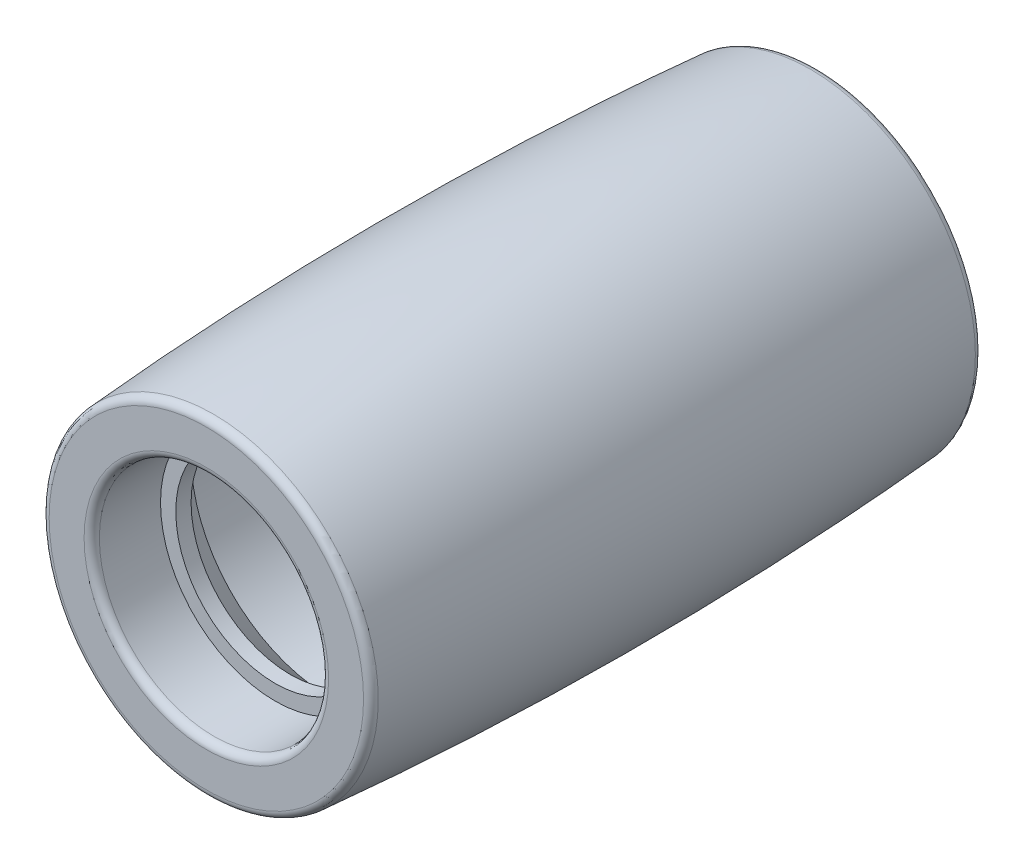
SolidWorks part; units mm, degrees
ref_plane "Ebene vorne" through (0, 0, 0) normal (0, 0, 1) x (1, 0, 0)
ref_plane "Ebene oben" through (0, 0, 0) normal (0, 1, 0) x (1, 0, 0)
ref_plane "Ebene rechts" through (0, 0, 0) normal (1, 0, 0) x (0, 0, -1)
sketch "Skizze1" plane through (0, 0, 0) normal (1, 0, 0) x (0, 0, -1)
  line L27 (0, 0) -> (99, 0) construction
  line L28 (89.5, 21.5) -> (89.5, 19.25) construction
  line L29 (81, 18.25) -> (83.1445, 19.25) construction
  line L30 (83.1445, 19.25) -> (89.5, 19.25) construction
  line L31 (42.3, 18.25) -> (81, 18.25) construction
  line L32 (42.3, 18.25) -> (42.3, 11) construction
  line L33 (42.3, 11) -> (39.3, 11) construction
  line L34 (39.3, 11) -> (39.3, 18.25) construction
  line L35 (20.5, 18.25) -> (39.3, 18.25) construction
  line L36 (20.5, 13) -> (27.7121, 20.2121) construction
  line L37 (18.5, 13) -> (20.5, 13) construction
  line L38 (18.5, 15) -> (18.5, 5) construction
  line L39 (18.5, 15) -> (9.5, 15) construction
  line L40 (9.5, 21.5) -> (9.5, 15) construction
  line L41 (0, 0) -> (99, 0) construction
  line L42 (89.5, 21.5) -> (89.5, 19.25)
  line L43 (81, 18.25) -> (83.1445, 19.25)
  line L44 (83.1445, 19.25) -> (89.5, 19.25)
  line L45 (42.3, 18.25) -> (81, 18.25)
  line L46 (42.3, 18.25) -> (42.3, 11)
  line L47 (42.3, 11) -> (39.3, 11)
  line L48 (39.3, 11) -> (39.3, 18.25)
  line L49 (25.75, 18.25) -> (39.3, 18.25)
  line L50 (20.5, 13) -> (25.75, 18.25)
  line L51 (18.5, 13) -> (20.5, 13)
  line L52 (18.5, 15) -> (18.5, 13)
  line L53 (18.5, 15) -> (9.5, 15)
  line L54 (9.5, 21.5) -> (9.5, 15)
  arc A2 (89.5, 21.5) -> (9.5, 21.5) centre (49.5, -511.0833) ccw construction
  arc A3 (89.5, 21.5) -> (9.5, 21.5) centre (49.5, -511.0833) ccw
revolve "Rotation1" add sketch "Skizze1" angle 360 about L27
sketch "Skizze4" plane through (0, 0, -39.3) normal (0, 0, 1) x (1, 0, 0)
  circle A0 centre (0, 0) radius 14 construction
  point P4 (0, 14)
hole_wizard "Durchgangsloch für M31" positions "Skizze4" profile "Skizze5" hole size "M3" standard "DIN"
sketch "Skizze5" plane through (0, 14, -39.3) normal (1, 0, 0) x (0, -1, 0)
  line L0 (0, 0) -> (0, 10.5815)
  line L1 (0, 10.5815) -> (1.8, 9.5)
  line L2 (1.8, 9.5) -> (1.8, 0)
  line L5 (1.8, 0) -> (0, 0)
  line L10 (0, 10.5815) -> (-1.8, 9.5) construction
  line L11 (0, -6.35) -> (0, 107.95) construction
  dimension "Bohrerdurchmesser" = 3.6
  dimension "Bohrungstiefe" = 9.5
  dimension "Spitzenwinkel" = 118
pattern_circular "Kreismuster2" count 4 over 360 about axis through (0, 0, 0) along (0, 0, 1) of "Durchgangsloch für M31"
fillet "Verrundung1" radius 1 3 edges at (21.5, 0, -89.5) (21.5, 0, -9.5) (15, 0, -9.5)
